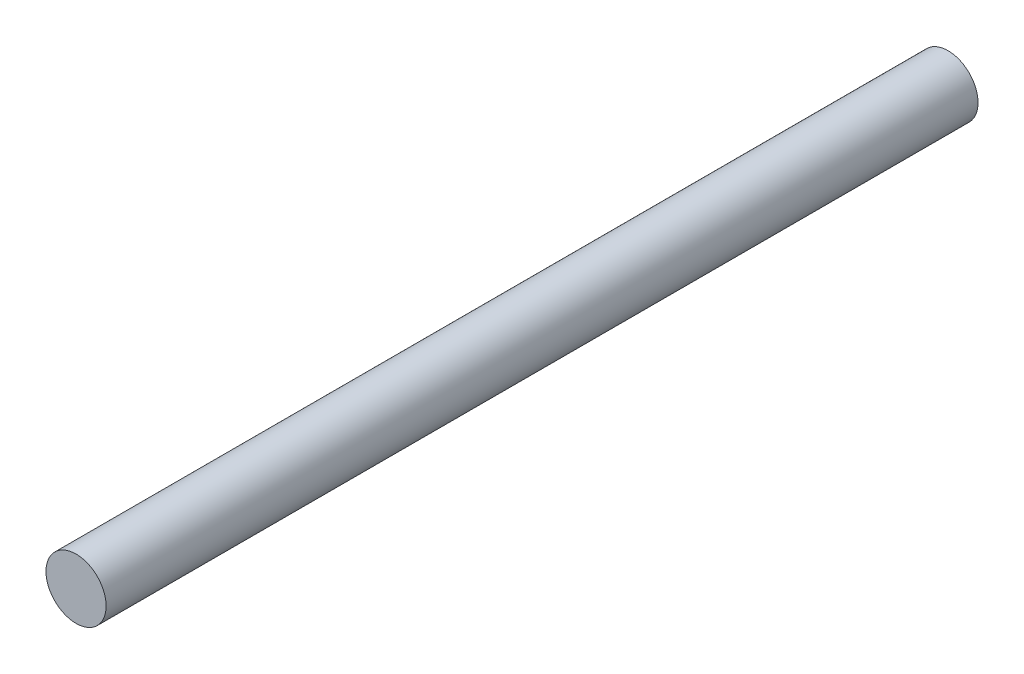
SolidWorks part; units mm, degrees
material "Otomat Oirinci,  UNS C36000"
ref_plane "Ön Düzlem" through (0, 0, 0) normal (0, 0, 1) x (1, 0, 0)
ref_plane "Üst Düzlem" through (0, 0, 0) normal (0, 1, 0) x (1, 0, 0)
ref_plane "Sağ Düzlem" through (0, 0, 0) normal (1, 0, 0) x (0, 0, -1)
sketch "Çizim1" plane through (0, 0, 0) normal (0, 0, 1) x (1, 0, 0)
  circle A0 centre (0, 0) radius 2
  dimension "D1" = 4
extrude "Yükseklik-Ekstrüzyon1" add sketch "Çizim1" along normal blind 58
sketch "Çizim3" plane through (0, 0, 0) normal (0, 0, -1) x (-1, 0, 0)
  circle A0 centre (0, 0) radius 1.75
  dimension "D1" = 3.5
extrude "Kes-Ekstrüzyon1" cut sketch "Çizim3" against normal blind 3
